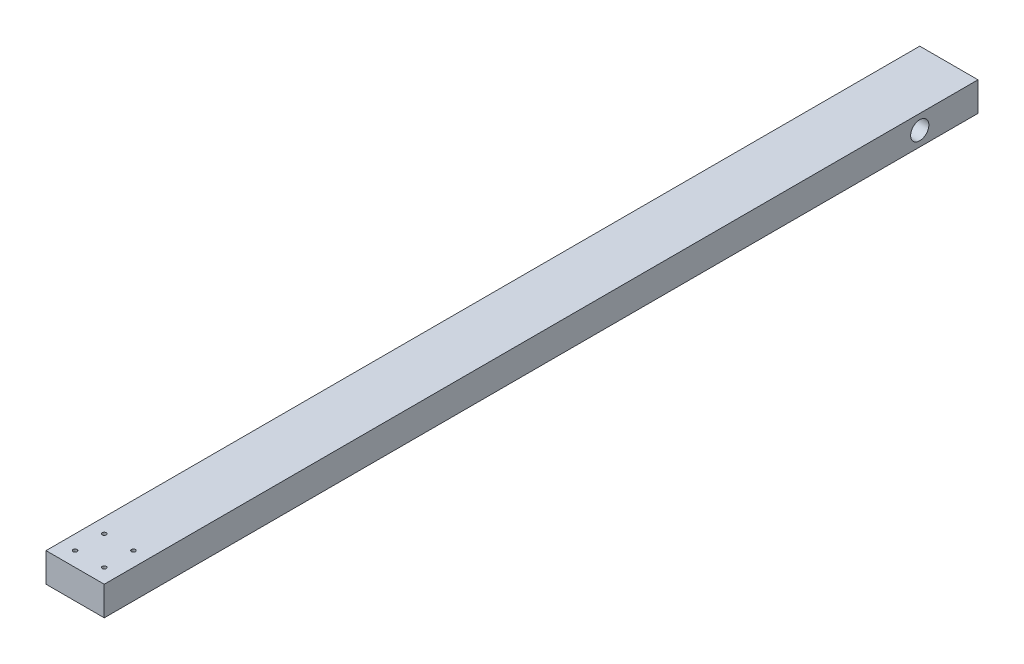
SolidWorks part; units mm, degrees
ref_plane "Front Plane" through (0, 0, 0) normal (0, 0, 1) x (1, 0, 0)
ref_plane "Top Plane" through (0, 0, 0) normal (0, 1, 0) x (1, 0, 0)
ref_plane "Right Plane" through (0, 0, 0) normal (1, 0, 0) x (0, 0, -1)
sketch "Sketch1" plane through (0, 0, 0) normal (0, 0, 1) x (1, 0, 0)
  line L1 (-50.8, 25.4) -> (50.8, 25.4)
  line L2 (-50.8, 25.4) -> (-50.8, -25.4)
  line L3 (-50.8, -25.4) -> (50.8, -25.4)
  line L4 (50.8, 25.4) -> (50.8, -25.4)
  line L5 (-50.8, 25.4) -> (50.8, -25.4) construction
  line L6 (-50.8, -25.4) -> (50.8, 25.4) construction
  point P0 (0, 0)
  dimension "D1" = 50.8
  dimension "D2" = 101.6
extrude "Boss-Extrude1" add sketch "Sketch1" along normal blind 1524
sketch "Sketch2" plane through (0, 25.4, 0) normal (0, 1, 0) x (1, 0, 0)
  line L0 (50.8, -1524) -> (-50.8, -1524) construction
  line L1 (-25.4, -1447.8) -> (25.4, -1447.8) construction
  line L2 (-25.4, -1447.8) -> (-25.4, -1498.6) construction
  line L3 (-25.4, -1498.6) -> (25.4, -1498.6) construction
  line L4 (25.4, -1447.8) -> (25.4, -1498.6) construction
  line L5 (-25.4, -1447.8) -> (25.4, -1498.6) construction
  line L6 (-25.4, -1498.6) -> (25.4, -1447.8) construction
  circle A0 centre (-25.4, -1447.8) radius 3.4925
  circle A1 centre (25.4, -1447.8) radius 3.4925
  circle A2 centre (25.4, -1498.6) radius 3.4925
  circle A3 centre (-25.4, -1498.6) radius 3.4925
  point P0 (0, -1473.2)
  dimension "D4" = 6.985
  dimension "D1" = 50.8
  dimension "D2" = 50.8
  dimension "D3" = 25.4
extrude "Cut-Extrude1" cut sketch "Sketch2" against normal up to surface (50.8 mm away) up to face at (0, -25.4, 762)
sketch "Sketch3" plane through (50.8, 0, 0) normal (1, 0, 0) x (0, 0, -1)
  line L0 (0, -25.4) -> (0, 25.4) construction
  circle A0 centre (-101.6, 0) radius 15.875
  point P4 (0, 0)
  dimension "D2" = 31.75
  dimension "D1" = 101.6
extrude "Cut-Extrude2" cut sketch "Sketch3" against normal up to surface (101.6 mm away) up to face at (-50.8, 0, 762)
